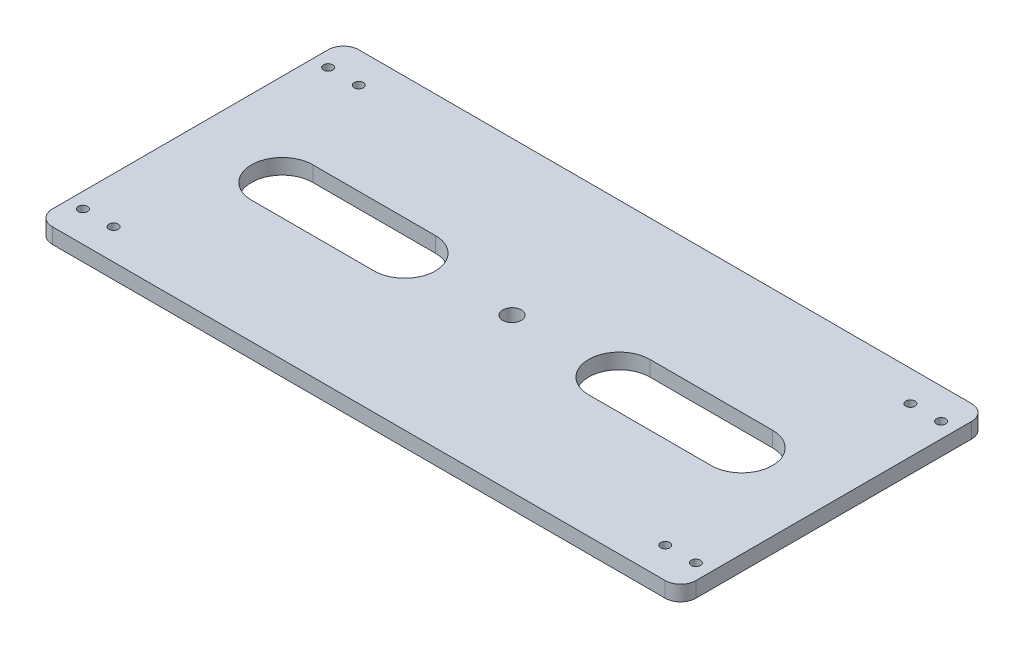
SolidWorks part; units mm, degrees
ref_plane "前视基准面" through (0, 0, 0) normal (0, 0, 1) x (1, 0, 0)
ref_plane "上视基准面" through (0, 0, 0) normal (0, 1, 0) x (1, 0, 0)
ref_plane "右视基准面" through (0, 0, 0) normal (1, 0, 0) x (0, 0, -1)
other "Configuration Table"
sketch "草图1" plane through (0, 0, 0) normal (0, 1, 0) x (1, 0, 0)
  line L1 (0, 0) -> (210, 0)
  line L2 (0, 0) -> (0, -100)
  line L3 (0, -100) -> (210, -100)
  line L4 (210, 0) -> (210, -100)
  dimension "D1" = 210
  dimension "D2" = 100
extrude "凸台-拉伸1" add sketch "草图1" along normal blind 5
sketch "草图2" plane through (0, 5, 0) normal (0, 1, 0) x (1, 0, 0)
  line L0 (0, -50) -> (210, -50) construction
  line L1 (0, 0) -> (0, -100) construction
  line L2 (210, -100) -> (210, 0) construction
  line L3 (105, 0) -> (105, -100) construction
  line L4 (210, 0) -> (0, 0) construction
  line L5 (0, -100) -> (210, -100) construction
  line L6 (30, -50) -> (70, -50) construction
  line L7 (30, -40) -> (70, -40)
  line L8 (30, -60) -> (70, -60)
  line L9 (140, -50) -> (180, -50) construction
  line L10 (140, -40) -> (180, -40)
  line L11 (140, -60) -> (180, -60)
  arc A0 (30, -40) -> (30, -60) centre (30, -50) ccw
  arc A1 (70, -60) -> (70, -40) centre (70, -50) ccw
  arc A2 (140, -40) -> (140, -60) centre (140, -50) ccw
  arc A3 (180, -60) -> (180, -40) centre (180, -50) ccw
  point P12 (105, -50)
  point P15 (50, -50)
  point P20 (160, -50)
  dimension "D3" = 10
  dimension "D1" = 35
  dimension "D2" = 40
  dimension "D4" = 35
extrude "切除-拉伸1" cut sketch "草图2" against normal blind 40
sketch "草图4" plane through (0, 5, 0) normal (0, 1, 0) x (1, 0, 0)
  circle A0 centre (105, -50) radius 3
  dimension "D1" = 6
extrude "切除-拉伸3" cut sketch "草图4" against normal blind 20
sketch "草图8" plane through (0, 5, 0) normal (0, 1, 0) x (1, 0, 0)
  line L0 (0, 0) -> (0, -100) construction
  line L1 (210, 0) -> (0, 0) construction
  line L2 (105, 0) -> (105, -100) construction
  line L3 (0, -100) -> (210, -100) construction
  line L4 (0, -50) -> (210, -50) construction
  line L5 (210, -100) -> (210, 0) construction
  line L6 (5, -10) -> (15, -10) construction
  circle A0 centre (5, -10) radius 1.5
  circle A1 centre (205, -10) radius 1.5
  circle A2 centre (205, -90) radius 1.5
  circle A3 centre (5, -90) radius 1.5
  circle A4 centre (15, -10) radius 1.5
  circle A5 centre (15, -90) radius 1.5
  circle A6 centre (195, -90) radius 1.5
  circle A7 centre (195, -10) radius 1.5
  dimension "D1" = 3
  dimension "D2" = 5
  dimension "D3" = 10
  dimension "D5" = 10
  dimension "D4" = 2
extrude "切除-拉伸4" cut sketch "草图8" against normal blind 20
fillet "圆角1" radius 5 4 edges at (0, 2.5, 0) (0, 2.5, 100) (210, 2.5, 100) (210, 2.5, 0)
